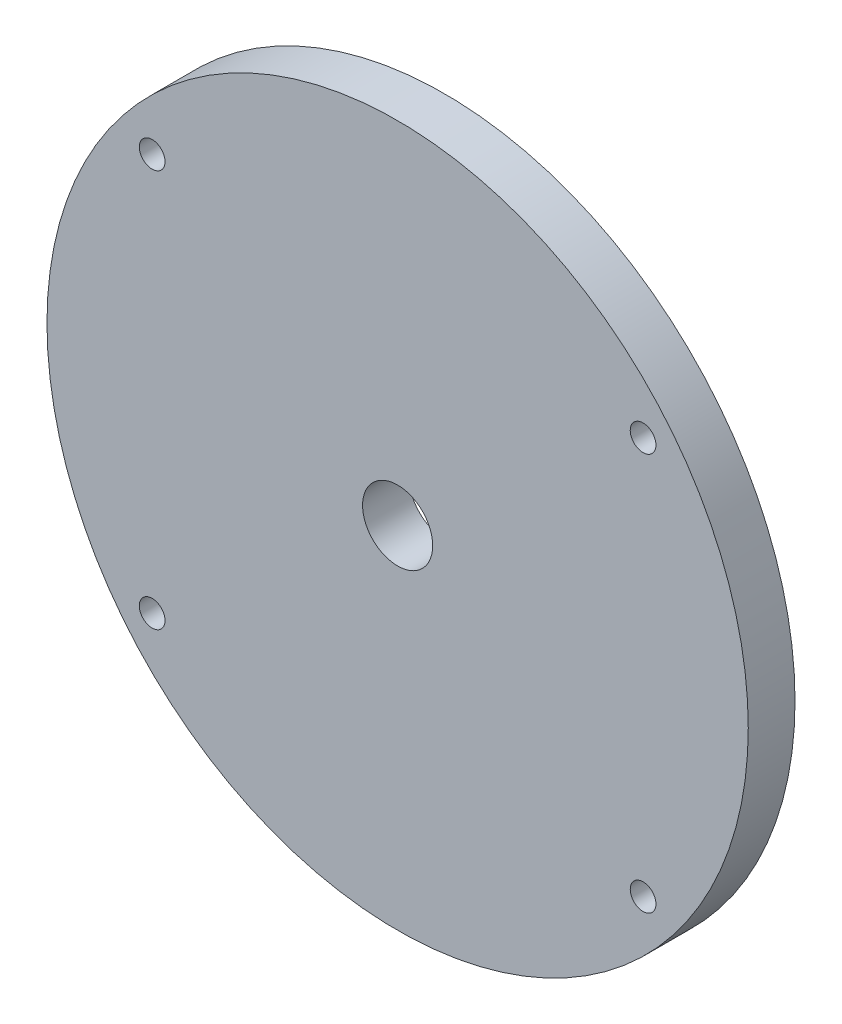
SolidWorks part; units mm, degrees
material "6061 Alloy"
ref_plane "Front Plane" through (0, 0, 0) normal (1, 0, 0) x (0, 1, 0)
ref_plane "Top Plane" through (0, 0, 0) normal (0, 0, 1) x (0, 1, 0)
ref_plane "Right Plane" through (0, 0, 0) normal (0, 1, 0) x (-1, 0, 0)
sketch "Sketch1" plane through (0, 0, 0) normal (0, 0, 1) x (0, 1, 0)
  circle A0 centre (0, 0) radius 75
  circle A1 centre (0, 0) radius 7.5
  dimension "D1" = 150
  dimension "D2" = 15
extrude "Boss-Extrude1" add sketch "Sketch1" along normal blind 10
sketch "Sketch2" plane through (0, 0, 10) normal (0, 0, 1) x (1, 0, 0)
  line L1 (-52.5, -42.5) -> (52.5, -42.5) construction
  line L2 (-52.5, -42.5) -> (-52.5, 42.5) construction
  line L3 (-52.5, 42.5) -> (52.5, 42.5) construction
  line L4 (52.5, -42.5) -> (52.5, 42.5) construction
  line L5 (-52.5, -42.5) -> (52.5, 42.5) construction
  line L6 (-52.5, 42.5) -> (52.5, -42.5) construction
  circle A0 centre (-52.5, 42.5) radius 1.5
  circle A1 centre (52.5, 42.5) radius 1.5
  circle A2 centre (52.5, -42.5) radius 1.5
  circle A3 centre (-52.5, -42.5) radius 1.5
  point P0 (0, 0)
  dimension "D3" = 3
  dimension "D1" = 105
  dimension "D2" = 85
extrude "Cut-Extrude1" cut sketch "Sketch2" against normal through all
hole_wizard "CSK for M5 Flat Head Machine Screw1" positions "3DSketch1" profile "Sketch3" countersink size "M5" standard "ANSI Metric" end condition through all
sketch3d "3DSketch1"
  line L0 (-52.5, -42.5, 0) -> (-52.5, -42.5, 10) construction
  line L1 (52.5, -42.5, 0) -> (52.5, -42.5, 10) construction
  line L2 (52.5, 42.5, 0) -> (52.5, 42.5, 10) construction
  line L3 (-52.5, 42.5, 0) -> (-52.5, 42.5, 10) construction
  point P0 (-52.5, -42.5, 0)
  point P4 (52.5, -42.5, 0)
  point P8 (52.5, 42.5, 0)
  point P12 (-52.5, 42.5, 0)
sketch "Sketch3" plane through (-52.5, -42.5, 0) normal (1, 0, 0) x (0, 1, 0)
  line L0 (0, 0) -> (0, 10)
  line L1 (0, 10) -> (2.75, 10)
  line L2 (2.75, 10) -> (2.75, 2.45)
  line L3 (2.75, 2.45) -> (5.2, 0)
  line L5 (5.2, 0) -> (0, 0)
  line L6 (-2.75, 2.45) -> (-5.2, 0) construction
  line L11 (0, -6.35) -> (0, 107.95) construction
  dimension "Thru Hole Dia." = 5.5
  dimension "Thru Hole Depth" = 10
  dimension "Near C'Sink Dia." = 10.4
  dimension "Near C'Sink Angle" = 90
